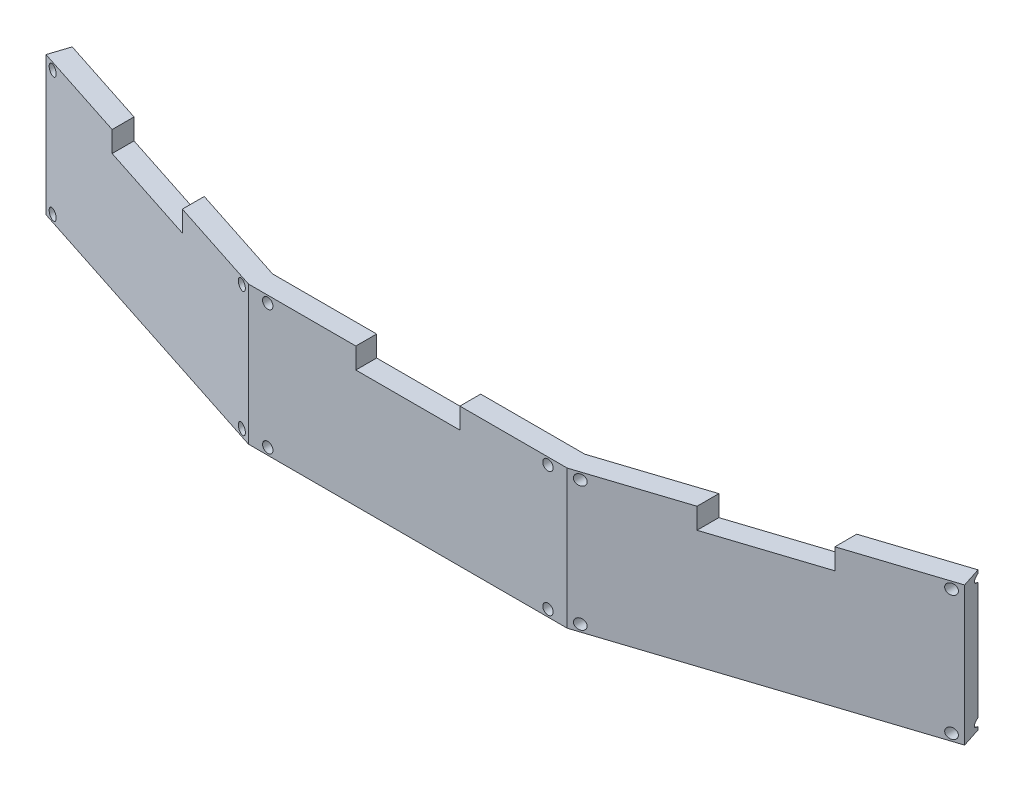
SolidWorks part; units mm, degrees
ref_plane "Front Plane" through (0, 0, 0) normal (0, 0, 1) x (1, 0, 0)
ref_plane "Top Plane" through (0, 0, 0) normal (0, 1, 0) x (1, 0, 0)
ref_plane "Right Plane" through (0, 0, 0) normal (1, 0, 0) x (0, 0, -1)
sketch "Sketch2" plane through (0, 0, 0) normal (0, 1, 0) x (1, 0, 0)
  line L0 (-22.5, 0) -> (22.5, 0)
  line L1 (-22.5, 0) -> (-65.2975, 13.9058)
  line L2 (-1001.8081, 0) -> (48998.1919, 0) construction
  line L3 (0, -1000) -> (0, 49000) construction
  line L4 (22.5, 0) -> (65.2975, 13.9058)
  point P3 (0, 0)
  dimension "D1" = 45
  dimension "D2" = 45
  dimension "D3" = 18
extrude "Extrude-Thin1" add sketch "Sketch2" against normal blind 20 thin
sketch "Sketch3" plane through (0, 0, 3) normal (0, 0, 1) x (1, 0, 0)
  line L0 (-22.9752, 0) -> (22.9752, 0) construction
  line L1 (-7.5, 0) -> (7.5, 0)
  line L2 (-7.5, 0) -> (-7.5, -3)
  line L3 (-7.5, -3) -> (7.5, -3)
  line L4 (7.5, 0) -> (7.5, -3)
  line L5 (-44.5999, 0) -> (-44.5999, -20) construction
  line L6 (-66.2246, 0) -> (-22.9752, 0) construction
  line L7 (-66.2246, -20) -> (-22.9752, -20) construction
  line L8 (-44.5999, -20) -> (44.5999, -20) construction
  line L9 (22.9752, -20) -> (66.2246, -20) construction
  line L10 (44.5999, -20) -> (44.5999, 0) construction
  line L11 (22.9752, 0) -> (66.2246, 0) construction
  line L12 (0, -1000) -> (0, 49000) construction
  line L13 (37.0999, 0) -> (52.0999, 0)
  line L14 (37.0999, 0) -> (37.0999, -3)
  line L15 (37.0999, -3) -> (52.0999, -3)
  line L16 (52.0999, 0) -> (52.0999, -3)
  line L17 (-37.0999, 0) -> (-37.0999, -3)
  line L18 (-37.0999, -3) -> (-52.0999, -3)
  line L19 (-52.0999, 0) -> (-52.0999, -3)
  line L20 (-37.0999, 0) -> (-52.0999, 0)
  line L21 (-64.7999, -1) -> (-24.3999, -1) construction
  line L22 (-933.7754, -10) -> (49066.2246, -10) construction
  line L23 (66.2246, -20) -> (66.2246, 0) construction
  line L28 (-20.2, -1) -> (-20.2, -19) construction
  line L29 (-20.2, -19) -> (20.2, -19) construction
  line L30 (20.2, -19) -> (20.2, -1) construction
  line L31 (20.2, -1) -> (-20.2, -1) construction
  circle A0 centre (-64.7999, -1) radius 0.75
  circle A1 centre (-24.3999, -1) radius 0.75
  circle A2 centre (-24.3999, -19) radius 0.75
  circle A3 centre (-64.7999, -19) radius 0.75
  circle A4 centre (64.7999, -1) radius 0.75
  circle A5 centre (24.3999, -1) radius 0.75
  circle A6 centre (24.3999, -19) radius 0.75
  circle A7 centre (64.7999, -19) radius 0.75
  circle A8 centre (-20.2, -1) radius 0.75
  circle A9 centre (-20.2, -19) radius 0.75
  circle A10 centre (20.2, -19) radius 0.75
  circle A11 centre (20.2, -1) radius 0.75
  point P6 (0, 0)
  point P26 (44.5999, 0)
  point P35 (-44.5999, -1)
  point P41 (66.2246, -10)
  dimension "D3" = 1.5
  dimension "D4" = 40.4
  dimension "D5" = 18
  dimension "D6" = 40.4
  dimension "D1" = 15
  dimension "D2" = 3
extrude "Cut-Extrude1" cut sketch "Sketch3" against normal through all
